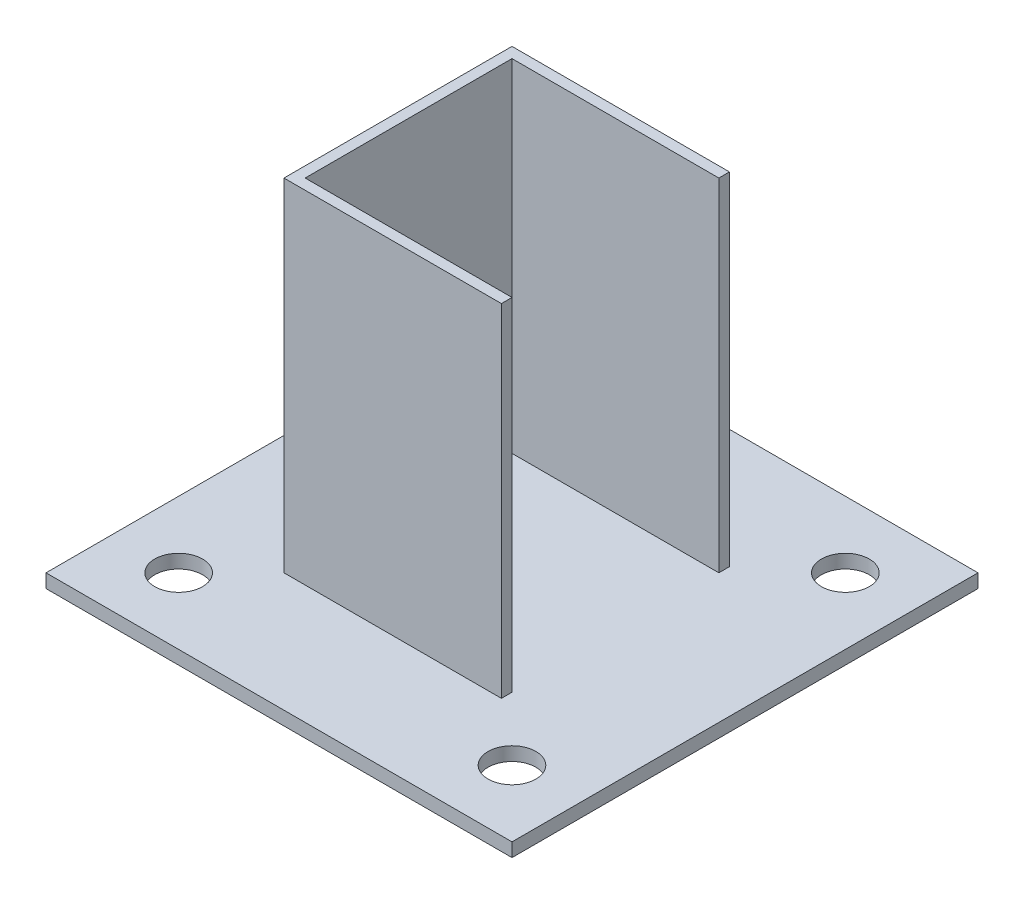
SolidWorks part; units mm, degrees
ref_plane "前视基准面" through (0, 0, 0) normal (0, 0, 1) x (1, 0, 0)
ref_plane "上视基准面" through (0, 0, 0) normal (0, 1, 0) x (1, 0, 0)
ref_plane "右视基准面" through (0, 0, 0) normal (1, 0, 0) x (0, 0, -1)
sketch "草图1" plane through (0, 0, 0) normal (0, 1, 0) x (1, 0, 0)
  line L1 (-68.15, 68.15) -> (68.15, 68.15)
  line L2 (-68.15, 68.15) -> (-68.15, -68.15)
  line L3 (-68.15, -68.15) -> (68.15, -68.15)
  line L4 (68.15, 68.15) -> (68.15, -68.15)
  line L5 (-68.15, 68.15) -> (68.15, -68.15) construction
  line L6 (-68.15, -68.15) -> (68.15, 68.15) construction
  point P0 (0, 0)
  dimension "D1" = 136.3
extrude "凸台-拉伸1" add sketch "草图1" along normal blind 4
sketch "草图2" plane through (0, 4, 0) normal (0, 1, 0) x (1, 0, 0)
  line L0 (30.25, 30.25) -> (-30.25, 30.25)
  line L1 (-30.25, 30.25) -> (-30.25, -30.25)
  line L2 (-30.25, -30.25) -> (30.25, -30.25)
  line L3 (30.25, -30.25) -> (30.25, -33.35)
  line L4 (30.25, -33.35) -> (-33.35, -33.35)
  line L5 (-33.35, -33.35) -> (-33.35, -1.55)
  line L6 (-33.35, 33.35) -> (30.25, 33.35)
  line L7 (30.25, 33.35) -> (30.25, 30.25)
  line L8 (-30.25, 30.25) -> (30.25, -30.25) construction
  line L9 (0, 0) -> (-100.3402, 0) construction
  line L10 (-33.35, 1.55) -> (-63.85, 1.55)
  line L12 (-33.35, -1.55) -> (-63.85, -1.55)
  line L13 (-63.85, 1.55) -> (-63.85, -1.55)
  line L14 (-33.35, 1.55) -> (-33.35, 33.35)
  point P2 (0, 0)
  point P16 (-63.85, 0)
  dimension "D1" = 3.1
  dimension "D2" = 3.1
  dimension "D3" = 3.1
  dimension "D4" = 66.7
  dimension "D5" = 60.5
  dimension "D6" = 63.6
  dimension "D7" = 30.5
  dimension "D8" = 3.1
extrude "凸台-拉伸2" add sketch "草图2" along normal blind 100
sketch "草图3" plane through (0, 0, 1.55) normal (0, 0, 1) x (1, 0, 0)
  line L0 (-63.85, 4) -> (-33.35, 72)
  line L1 (-33.35, 104) -> (-33.35, 4) construction
  line L2 (-33.35, 72) -> (-33.35, 104)
  line L3 (-33.35, 104) -> (-63.85, 104)
  line L4 (-63.85, 104) -> (-63.85, 4)
  line L5 (-63.85, 4) -> (-33.35, 4) construction
  dimension "D1" = 68
extrude "切除-拉伸1" cut sketch "草图3" against normal blind 100
sketch "草图5" plane through (0, 4, 0) normal (0, 1, 0) x (1, 0, 0)
  line L1 (-48.75, -48.75) -> (48.75, -48.75) construction
  line L2 (-48.75, -48.75) -> (-48.75, 48.75) construction
  line L3 (-48.75, 48.75) -> (48.75, 48.75) construction
  line L4 (48.75, -48.75) -> (48.75, 48.75) construction
  line L5 (-48.75, -48.75) -> (48.75, 48.75) construction
  line L6 (-48.75, 48.75) -> (48.75, -48.75) construction
  circle A0 centre (48.75, 48.75) radius 7
  circle A1 centre (48.75, -48.75) radius 7
  circle A2 centre (-48.75, -48.75) radius 7
  circle A3 centre (-48.75, 48.75) radius 7
  point P0 (0, 0)
  point P16 (0, 0)
  dimension "D2" = 14
  dimension "D1" = 97.5
  dimension "D3" = 4
extrude "切除-拉伸2" cut sketch "草图5" against normal blind 100
